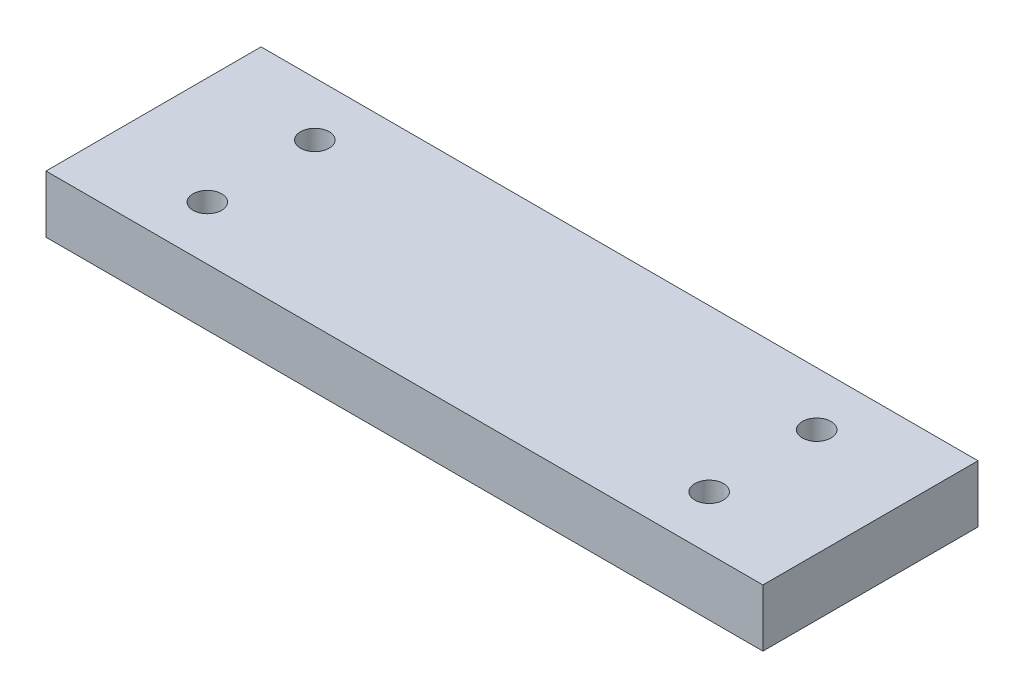
SolidWorks part; units mm, degrees
ref_plane "Front Plane" through (0, 0, 0) normal (0, 0, 1) x (1, 0, 0)
ref_plane "Top Plane" through (0, 0, 0) normal (0, 1, 0) x (1, 0, 0)
ref_plane "Right Plane" through (0, 0, 0) normal (1, 0, 0) x (0, 0, -1)
sketch "Sketch1" plane through (0, 0, 0) normal (0, 1, 0) x (1, 0, 0)
  line L0 (35, 7.5) -> (35, -7.5) construction
  line L1 (-50, 15) -> (50, 15)
  line L2 (-50, 15) -> (-50, -15)
  line L3 (-50, -15) -> (50, -15)
  line L4 (50, 15) -> (50, -15)
  line L5 (-50, 15) -> (50, -15) construction
  line L6 (-50, -15) -> (50, 15) construction
  line L7 (0, 15) -> (0, -15) construction
  circle A0 centre (35, 7.5) radius 2
  circle A1 centre (35, -7.5) radius 2
  circle A2 centre (-35, -7.5) radius 2
  circle A3 centre (-35, 7.5) radius 2
  point P0 (0, 0)
  dimension "D3" = 4
  dimension "D4" = 4
  dimension "D6" = 7.5
  dimension "D1" = 100
  dimension "D2" = 30
  dimension "D5" = 15
  dimension "D7" = 15
extrude "Boss-Extrude1" add sketch "Sketch1" along normal blind 8
